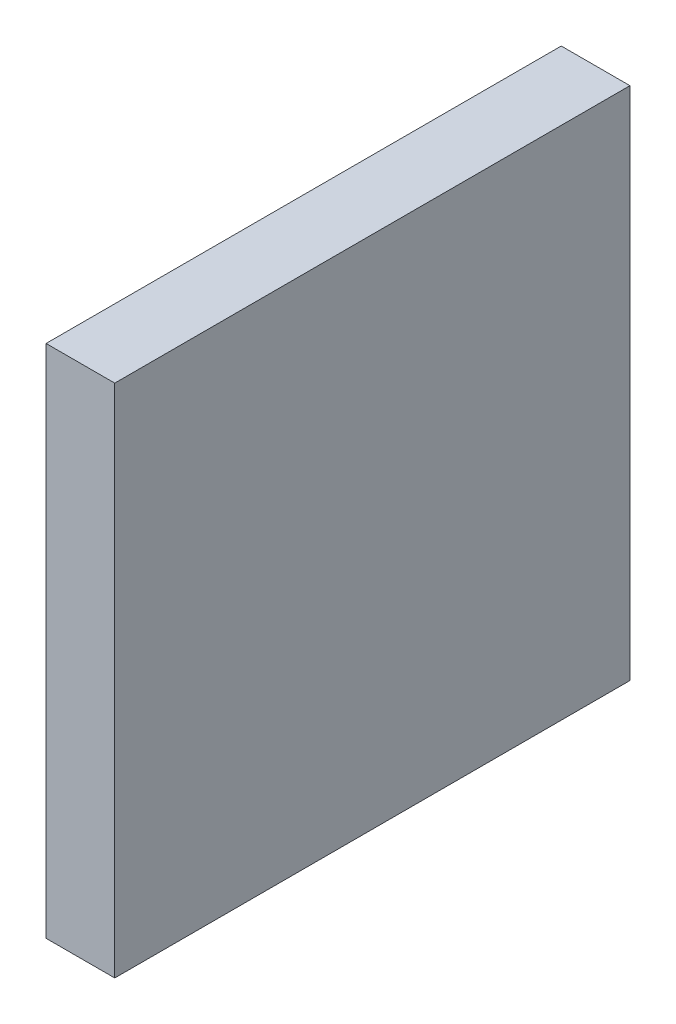
SolidWorks part; units mm, degrees
material "ABS"
ref_plane "Ground_Plane" through (0, 0, 0) normal (0, 0, 1) x (1, 0, 0)
ref_plane "VehicleCentre_Plane" through (0, 0, 0) normal (0, 1, 0) x (1, 0, 0)
ref_plane "FrontAxle_Plane" through (0, 0, 0) normal (1, 0, 0) x (0, 0, -1)
sketch "Sketch1" plane through (0, 0, 0) normal (1, 0, 0) x (0, 0, -1)
  line L1 (13.5, -13.5) -> (-13.5, -13.5)
  line L2 (13.5, -13.5) -> (13.5, 13.5)
  line L3 (13.5, 13.5) -> (-13.5, 13.5)
  line L4 (-13.5, -13.5) -> (-13.5, 13.5)
  line L5 (13.5, -13.5) -> (-13.5, 13.5) construction
  line L6 (13.5, 13.5) -> (-13.5, -13.5) construction
  point P0 (0, 0)
  dimension "D1" = 27
extrude "Boss-Extrude1" add sketch "Sketch1" along normal blind 3.6
sketch "Sketch2" plane through (0, 0, 0) normal (-1, 0, 0) x (0, 0, 1)
  line L0 (-2.5, -7) -> (-2.5, -9)
  line L1 (-5.75, 9.5) -> (-9.25, 9.5)
  line L2 (-5.75, 9.5) -> (-5.75, -0.5)
  line L3 (-5.75, -0.5) -> (-9.25, -0.5)
  line L4 (-9.25, 9.5) -> (-9.25, -0.5)
  line L5 (-5.75, 9.5) -> (-9.25, -0.5) construction
  line L6 (-5.75, -0.5) -> (-9.25, 9.5) construction
  line L7 (9.25, 9.5) -> (5.75, 9.5)
  line L8 (9.25, 9.5) -> (9.25, -0.5)
  line L9 (9.25, -0.5) -> (5.75, -0.5)
  line L10 (5.75, 9.5) -> (5.75, -0.5)
  line L11 (9.25, 9.5) -> (5.75, -0.5) construction
  line L12 (9.25, -0.5) -> (5.75, 9.5) construction
  line L13 (-2.5, -9) -> (2.5, -9)
  line L14 (2.5, -9) -> (2.5, -7)
  line L15 (-13.5, 13.5) -> (13.5, 13.5) construction
  line L16 (-7.5, 4.5) -> (7.5, 4.5) construction
  arc A0 (-2.5, -7) -> (2.5, -7) centre (0, -7) cw
  point P0 (-7.5, 4.5)
  point P5 (7.5, 4.5)
  point P19 (0, 4.5)
  dimension "D6" = 2.5
  dimension "D1" = 4
  dimension "D2" = 3.5
  dimension "D3" = 10
  dimension "D4" = 15
  dimension "D5" = 2
  dimension "D7" = 7
extrude "Cut-Extrude1" cut sketch "Sketch2" against normal blind 3
